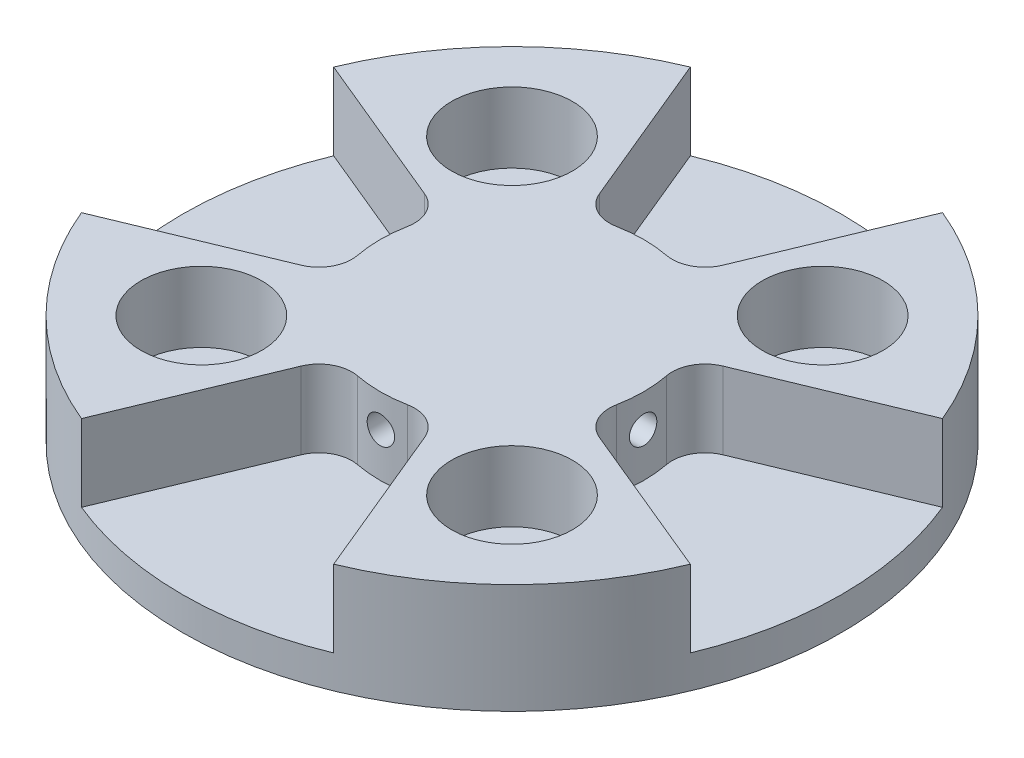
SolidWorks part; units mm, degrees
ref_plane "Front Plane" through (0, 0, 0) normal (0, 0, 1) x (1, 0, 0)
ref_plane "Top Plane" through (0, 0, 0) normal (0, 1, 0) x (1, 0, 0)
ref_plane "Right Plane" through (0, 0, 0) normal (1, 0, 0) x (0, 0, -1)
sketch "Sketch1" plane through (0, 0, 0) normal (0, 1, 0) x (1, 0, 0)
  circle A0 centre (0, 0) radius 30
  dimension "D1" = 60
extrude "Boss-Extrude1" add sketch "Sketch1" along normal blind 10
hole_wizard "CBORE for M6 Hex Socket Head Cap Screw1" positions "Sketch2" profile "Sketch3" counterbore size "M6" standard "ISO" end condition up to next
sketch "Sketch2" plane through (0, 10, 0) normal (0, 1, 0) x (1, 0, 0)
  line L1 (14.1421, 14.1421) -> (-14.1421, 14.1421)
  line L2 (-14.1421, 14.1421) -> (-14.1421, -14.1421)
  line L3 (-14.1421, -14.1421) -> (14.1421, -14.1421)
  line L4 (14.1421, -14.1421) -> (14.1421, 14.1421)
  circle A0 centre (0, 0) radius 20 construction
  point P3 (14.1421, 14.1421)
  point P4 (-14.1421, 14.1421)
  point P5 (-14.1421, -14.1421)
  point P6 (14.1421, -14.1421)
  dimension "D1" = 40
sketch "Sketch3" plane through (14.1421, 10, 14.1421) normal (1, 0, 0) x (0, 0, 1)
  line L0 (0, 0) -> (0, 10)
  line L1 (0, 10) -> (3.3, 10)
  line L3 (3.3, 10) -> (3.3, 6.4)
  line L4 (3.3, 6.4) -> (5.5, 6.4)
  line L5 (5.5, 6.4) -> (5.5, 0)
  line L7 (5.5, 0) -> (0, 0)
  line L11 (0, -6.35) -> (0, 107.95) construction
  dimension "Thru Hole Dia." = 6.6
  dimension "Thru Hole Depth" = 10
  dimension "C'Bore Dia." = 11
  dimension "C'Bore Depth" = 6.4
sketch "Sketch4" plane through (0, 10, 0) normal (0, 1, 0) x (1, 0, 0)
  line L0 (0, 0) -> (-11.4805, -27.7164)
  line L1 (0, 0) -> (11.4805, -27.7164)
  circle A0 centre (0, 0) radius 12
  circle A1 centre (0, 0) radius 30 construction
  circle M8 centre (0, 0) radius 30
  dimension "D1" = 18
  dimension "D2" = 45
extrude "Cut-Extrude1" cut sketch "Sketch4" against normal blind 7 contours A0 L0 L1 M8
ref_plane "Plane1" through (0, 0, 12) normal (0, 0, 1) x (1, 0, 0)
hole_wizard "M3 Tapped Hole1" positions "Sketch5" profile "Sketch6" tap size "M3" standard "ISO"
sketch "Sketch5" plane through (0, 0, 12) normal (0, 0, 1) x (1, 0, 0)
  line L0 (30, 10) -> (-30, 10) construction
  point P0 (0, 7)
  dimension "D1" = 3
sketch "Sketch6" plane through (0, 7, 12) normal (1, 0, 0) x (0, -1, 0)
  line L0 (0, 0) -> (0, 12.7511)
  line L1 (0, 12.7511) -> (1.25, 12)
  line L2 (1.25, 12) -> (1.25, 0)
  line L5 (1.25, 0) -> (0, 0)
  line L10 (0, 12.7511) -> (-1.25, 12) construction
  line L11 (0, -6.35) -> (0, 107.95) construction
  dimension "Tap Drill Dia." = 2.5
  dimension "Tap Drill Depth" = 12
  dimension "Drill Angle" = 118
cosmetic thread "Hole Thread2" parameters "D1"=6, "D2"=3
pattern_circular "CirPattern1" count 4 over 360 about axis through (0, 10, 0) along (0, 1, 0) of "Cut-Extrude1", "M3 Tapped Hole1"
ref_plane "Plane2" through (0, 0, 30) normal (0, 0, 1) x (1, 0, 0)
sketch "Sketch8" plane through (0, 0, 30) normal (0, 0, 1) x (1, 0, 0)
  circle A0 centre (0, 7) radius 3.25
  dimension "D1" = 6.5
extrude "Cut-Extrude2" [suppressed] cut sketch "Sketch8" against normal blind 3.4
fillet "Fillet1" radius 3 8 edges at (4.5922, 6.5, 11.0866) (-4.5922, 6.5, 11.0866) (-11.0866, 6.5, 4.5922) (-11.0866, 6.5, -4.5922) (-4.5922, 6.5, -11.0866) (4.5922, 6.5, -11.0866) (11.0866, 6.5, -4.5922) (11.0866, 6.5, 4.5922)
